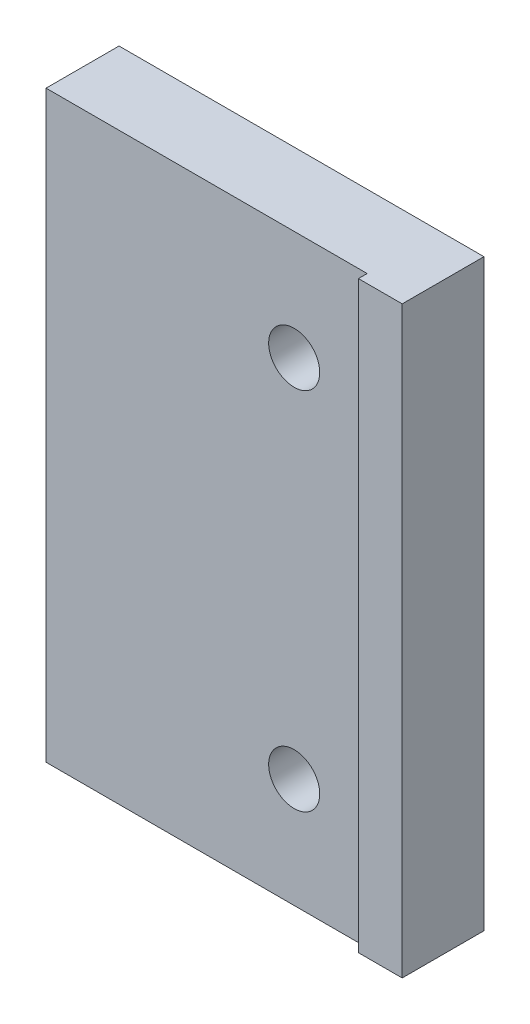
SolidWorks part; units mm, degrees
ref_plane "Front Plane" through (0, 0, 0) normal (0, 0, 1) x (1, 0, 0)
ref_plane "Top Plane" through (0, 0, 0) normal (0, 1, 0) x (1, 0, 0)
ref_plane "Right Plane" through (0, 0, 0) normal (1, 0, 0) x (0, 0, -1)
sketch "Sketch1" plane through (0, 0, 0) normal (0, 0, 1) x (1, 0, 0)
  line L0 (17, 32.5) -> (17, 7.5) construction
  line L1 (0, 0) -> (25, 0)
  line L2 (0, 0) -> (0, 40)
  line L3 (0, 40) -> (25, 40)
  line L4 (25, 0) -> (25, 40)
  line L5 (17, 7.5) -> (17, 0) construction
  line L6 (17, 32.5) -> (17, 40) construction
  circle A0 centre (17, 32.5) radius 1.75
  circle A1 centre (17, 7.5) radius 1.75
  dimension "D3" = 3.5
  dimension "D1" = 25
  dimension "D2" = 25
  dimension "D4" = 40
  dimension "D5" = 8
extrude "Boss-Extrude1" add sketch "Sketch1" along normal blind 5
sketch "Sketch2" plane through (0, 0, 5) normal (0, 0, 1) x (1, 0, 0)
  line L0 (0, 0) -> (25, 0) construction
  line L1 (25, 40) -> (22, 40)
  line L2 (25, 40) -> (25, 0)
  line L3 (25, 0) -> (22, 0)
  line L4 (22, 40) -> (22, 0)
  dimension "D1" = 3
extrude "Boss-Extrude2" add sketch "Sketch2" along normal blind 0.6
